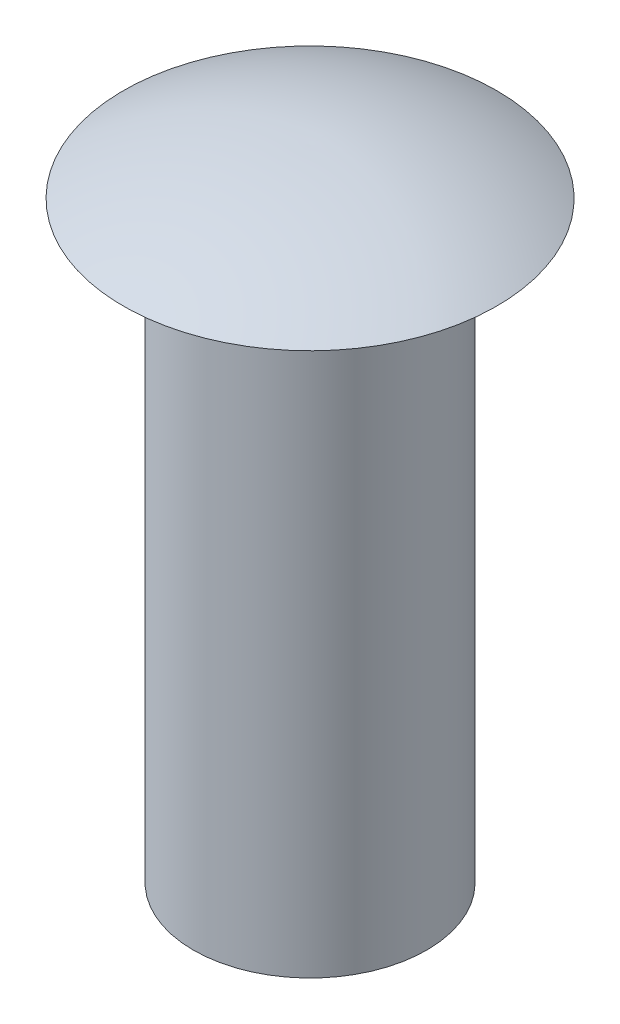
SolidWorks part; units mm, degrees
ref_plane "Front Plane" through (0, 0, 0) normal (0, 0, 1) x (1, 0, 0)
ref_plane "Top Plane" through (0, 0, 0) normal (0, 1, 0) x (1, 0, 0)
ref_plane "Right Plane" through (0, 0, 0) normal (1, 0, 0) x (0, 0, -1)
sketch "Sketch1" plane through (0, 0, 0) normal (0, 1, 0) x (1, 0, 0)
  circle A0 centre (0, 0) radius 2.5
  dimension "D1" = 5
extrude "Boss-Extrude1" add sketch "Sketch1" along normal blind 12.7
sketch "Sketch2" plane through (0, 0, 0) normal (0, 0, 1) x (1, 0, 0)
  line L0 (0, 12.7) -> (0, 13.7)
  line L1 (2.5, 12.7) -> (-2.5, 12.7) construction
  line L2 (0, 12.7) -> (4, 12.7)
  arc A0 (0, 13.7) -> (4, 12.7) centre (0.1229, 5.6915) cw
  dimension "D1" = 1
  dimension "D2" = 4
revolve "Revolve1" add sketch "Sketch2" angle 360 about L0
